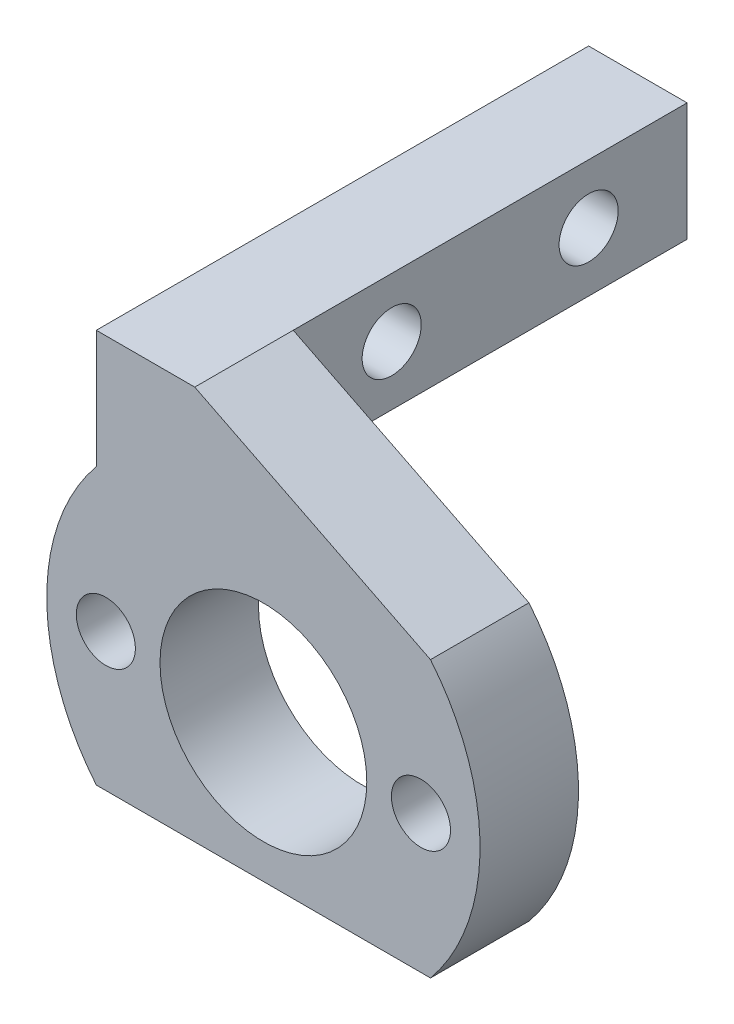
SolidWorks part; units mm, degrees
ref_plane "前视基准面" through (0, 0, 0) normal (0, 0, 1) x (1, 0, 0)
ref_plane "上视基准面" through (0, 0, 0) normal (0, 1, 0) x (1, 0, 0)
ref_plane "右视基准面" through (0, 0, 0) normal (1, 0, 0) x (0, 0, -1)
sketch "草图1" plane through (0, 0, 0) normal (1, 0, 0) x (0, 0, -1)
  line L0 (5, 3) -> (15, 3) construction
  line L1 (0, 0) -> (20, 0)
  line L2 (0, 0) -> (0, 6)
  line L3 (0, 6) -> (20, 6)
  line L4 (20, 0) -> (20, 6)
  circle A0 centre (5, 3) radius 1.5
  circle A1 centre (15, 3) radius 1.5
  point P9 (10, 3)
  point P10 (0, 3)
  point P11 (10, 0)
  dimension "D1" = 3
  dimension "D2" = 6
  dimension "D3" = 10
  dimension "D4" = 20
extrude "凸台-拉伸1" add sketch "草图1" along normal blind 5
sketch "草图2" plane through (0, 0, 0) normal (0, 0, 1) x (1, 0, 0)
  line L1 (0, -14) -> (16.9706, -14)
  line L2 (0, 0) -> (16.9706, 0)
  line L3 (0, 0) -> (0, 6)
  line L4 (0, 6) -> (5, 6)
  line L5 (5, 6) -> (16.9706, 0)
  arc A0 (0, 0) -> (0, -14) centre (8.4853, -7) ccw
  circle A1 centre (8.4853, -7) radius 5.25
  circle A2 centre (8.4853, -7) radius 8 construction
  circle A3 centre (0.4853, -7) radius 1.5
  circle A4 centre (16.4853, -7) radius 1.5
  arc A6 (16.9706, 0) -> (0, 0) centre (8.4853, -7) ccw construction
  arc A7 (16.9706, -14) -> (16.9706, 0) centre (8.4853, -7) ccw
  arc A8 (0, -14) -> (16.9706, -14) centre (8.4853, -7) ccw construction
  point P1 (-2.5147, -7)
  dimension "D1" = 11
  dimension "D2" = 10.5
  dimension "D4" = 16
  dimension "D5" = 3
  dimension "D3" = 14
extrude "凸台-拉伸2" add sketch "草图2" along normal blind 5
